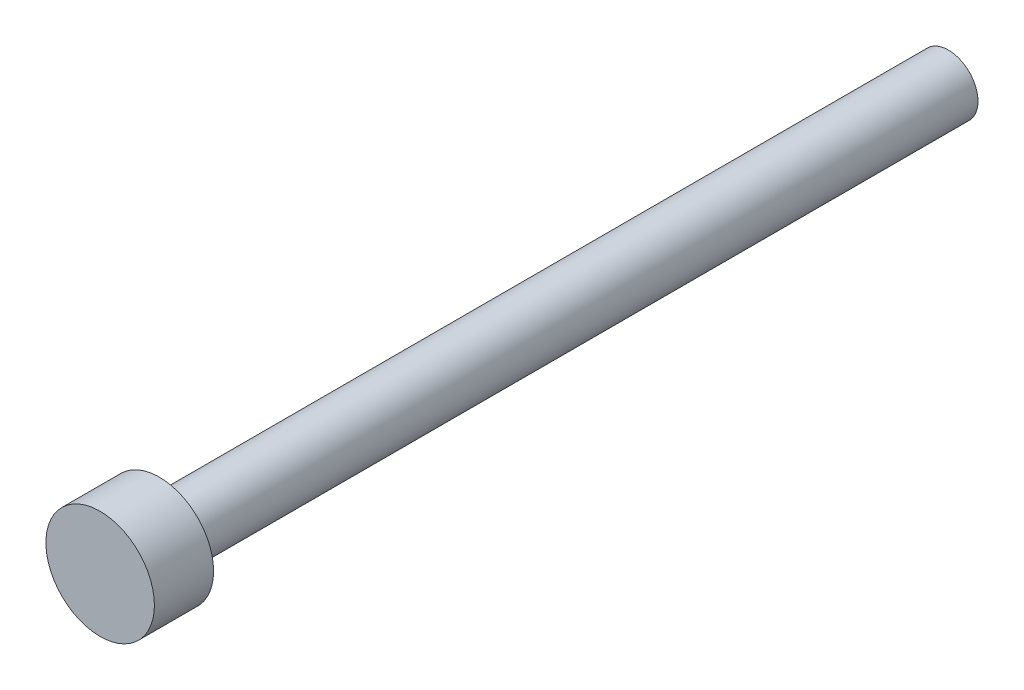
SolidWorks part; units mm, degrees
ref_plane "Front Plane" through (0, 0, 0) normal (0, 0, 1) x (1, 0, 0)
ref_plane "Top Plane" through (0, 0, 0) normal (0, 1, 0) x (1, 0, 0)
ref_plane "Right Plane" through (0, 0, 0) normal (1, 0, 0) x (0, 0, -1)
sketch "Shank_nominal_thread_envelope_profile" plane through (0, 0, 0) normal (0, 0, 1) x (1, 0, 0)
  circle A0 centre (0, 0) radius 1.5
  dimension "D1" = 3
extrude "Shank_nominal_thread_envelope" add sketch "Shank_nominal_thread_envelope_profile" along normal blind 40 from offset 40
sketch "Socket_head_envelope_profile" plane through (0, 0, 0) normal (0, 0, 1) x (1, 0, 0)
  circle A0 centre (0, 0) radius 2.75
  dimension "D1" = 5.5
extrude "Socket_head_envelope" add sketch "Socket_head_envelope_profile" along normal blind 3
